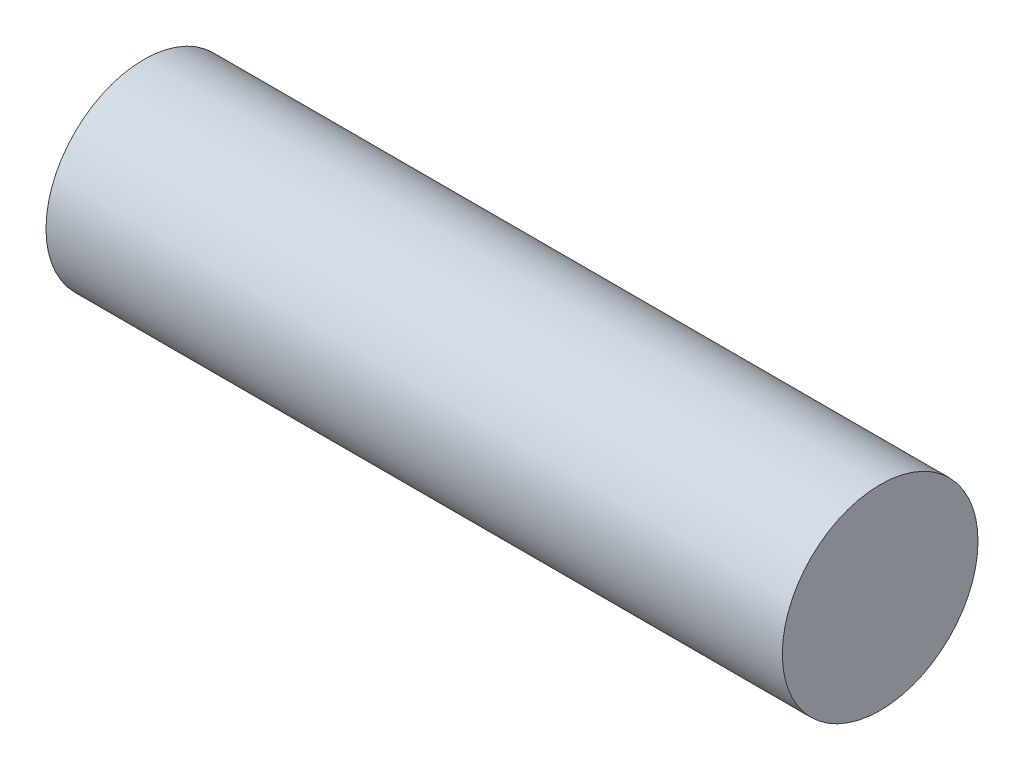
SolidWorks part; units mm, degrees
ref_plane "Front Plane" through (0, 0, 0) normal (0, 0, 1) x (1, 0, 0)
ref_plane "Top Plane" through (0, 0, 0) normal (0, 1, 0) x (1, 0, 0)
ref_plane "Right Plane" through (0, 0, 0) normal (1, 0, 0) x (0, 0, -1)
sketch "Sketch2" plane through (0, 0, 0) normal (1, 0, 0) x (0, 0, -1)
  circle A0 centre (0, 0) radius 9.3
  dimension "D1" = 18.6
extrude "Boss-Extrude1" add sketch "Sketch2" along normal blind 70
